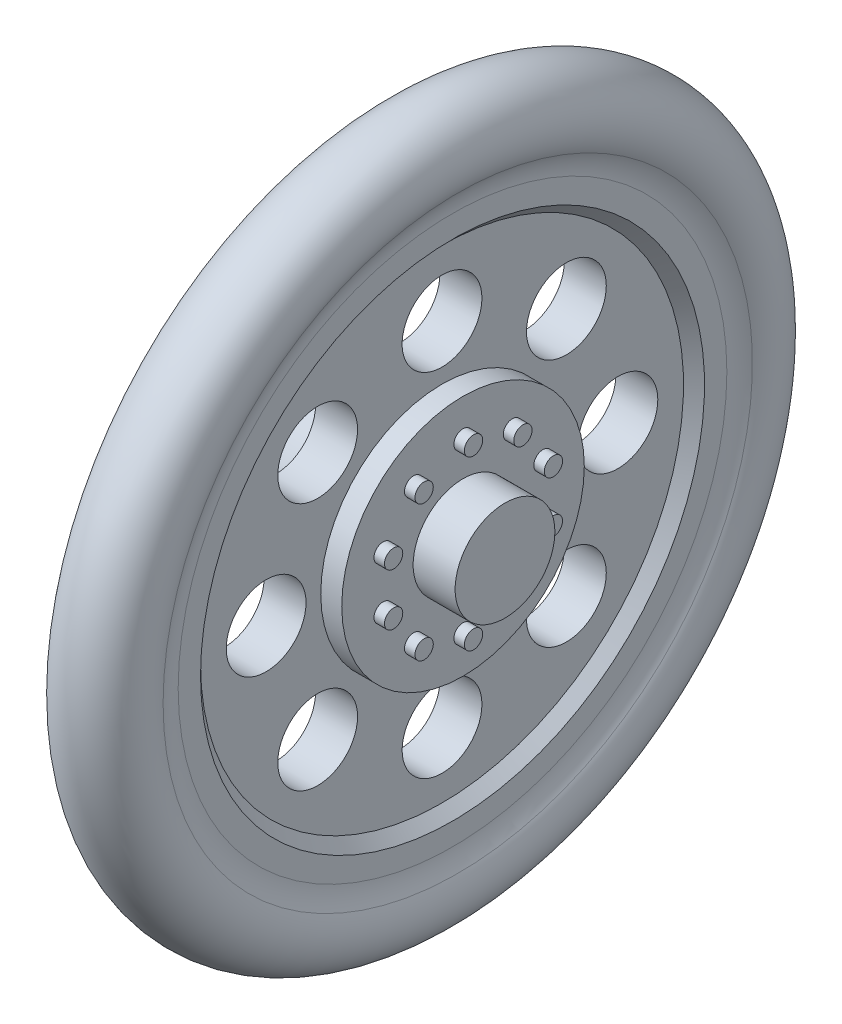
SolidWorks part; units mm, degrees
material "PE High Density"
ref_plane "Front Plane" through (0, 0, 0) normal (0, 0, 1) x (1, 0, 0)
ref_plane "Top Plane" through (0, 0, 0) normal (0, 1, 0) x (1, 0, 0)
ref_plane "Right Plane" through (0, 0, 0) normal (1, 0, 0) x (0, 0, -1)
sketch "Sketch1" plane through (0, 0, 0) normal (0, 0, 1) x (1, 0, 0)
  line L0 (0, 0) -> (17.1706, 0) construction
  line L1 (9.5, 0) -> (0, 0)
  line L2 (0, 0) -> (0, 3.1)
  line L3 (0, 3.1) -> (7.5, 3.1)
  line L4 (7.5, 3.1) -> (7.5, 11.5)
  line L5 (7.5, 7.7069) -> (9.5, 7.7069) construction
  line L6 (9.5, 11.5) -> (9.5, 0)
  line L7 (8.5, 7.7069) -> (8.5, 15) construction
  line L8 (10, 12) -> (9.5, 11.5)
  line L9 (7, 13.6771) -> (7, 12)
  line L10 (7, 12) -> (7.5, 11.5)
  line L11 (10, 13.6771) -> (10, 12)
  arc A0 (10, 13.6771) -> (7, 13.6771) centre (8.5, 15) ccw
  dimension "D1" = 4
  dimension "D3" = 34
  dimension "D5" = 6.5
  dimension "D2" = 2
  dimension "D4" = 6.2
  dimension "D6" = 23
  dimension "D7" = 0.5
  dimension "D8" = 45
revolve "Revolve1" add sketch "Sketch1" angle 360 about L0
fillet "Fillet1" radius 2 2 edges at (7, 0, 13.6771) (10, 0, 13.6771)
sketch "Sketch2" plane through (9.5, 0, 0) normal (1, 0, 0) x (0, 0, -1)
  circle A0 centre (0, 0) radius 5.775
  dimension "D1" = 11.55
extrude "Extrude1" add sketch "Sketch2" along normal blind 1
sketch "Sketch3" plane through (10.5, 0, 0) normal (1, 0, 0) x (0, 0, -1)
  circle A0 centre (0, 0) radius 2.375
  dimension "D1" = 4.75
extrude "Extrude2" add sketch "Sketch3" along normal blind 2
sketch "Sketch4" plane through (10.5, 0, 0) normal (1, 0, 0) x (0, 0, -1)
  circle A0 centre (0, 0) radius 4 construction
  circle A1 centre (0, 4) radius 0.435
  dimension "D1" = 0.87
  dimension "D2" = 8
extrude "Extrude3" add sketch "Sketch4" along normal blind 0.5
pattern_circular "CirPattern1" count 10 over 360 about axis through (0, 0, 0) along (1, 0, 0) of "Extrude3"
sketch "Sketch5" plane through (9.5, 0, 0) normal (1, 0, 0) x (0, 0, -1)
  circle A0 centre (0, 0) radius 8.375 construction
  circle A1 centre (0, 8.375) radius 1.9
  dimension "D1" = 3.8
  dimension "D2" = 16.75
extrude "Cut-Extrude1" cut sketch "Sketch5" against normal through all
pattern_circular "CirPattern2" count 8 over 360 about axis through (0, 0, 0) along (1, 0, 0) of "Cut-Extrude1"
sketch "Sketch6" plane through (0, 0, 0) normal (-1, 0, 0) x (0, 0, 1)
  circle A0 centre (0, 0) radius 1.63
  dimension "D1" = 3.26
extrude "Cut-Extrude2" cut sketch "Sketch6" against normal offset from surface (10.9125 mm away) 1.5875 up to face at (12.5, 0, -2.375)
